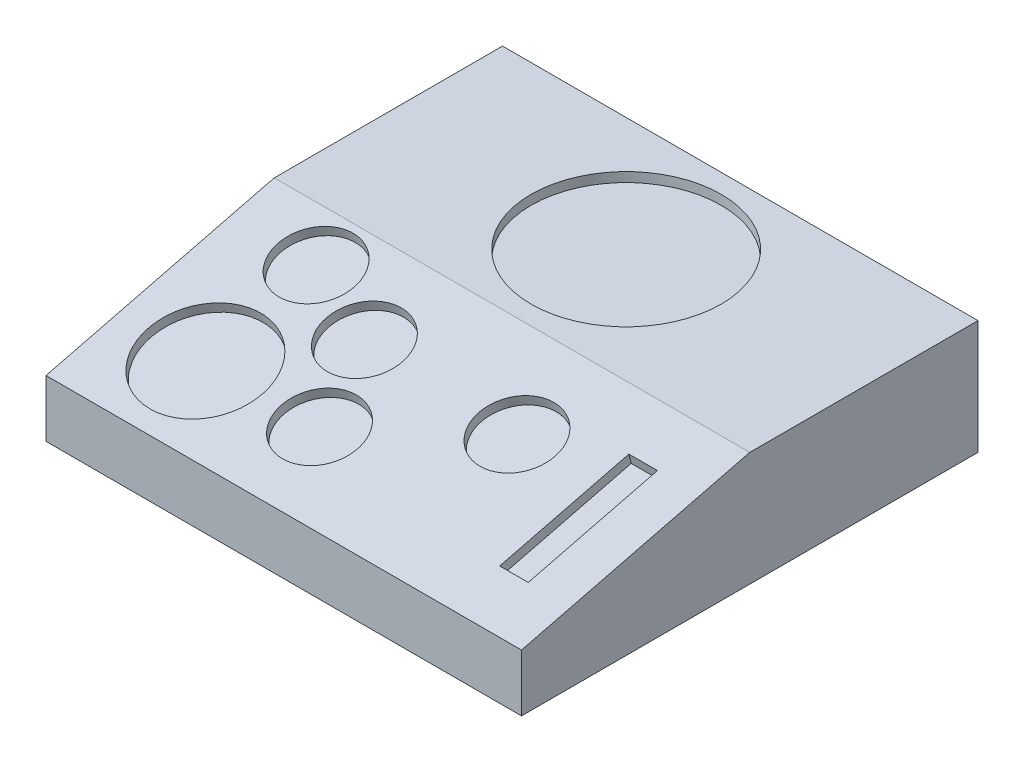
SolidWorks part; units mm, degrees
ref_plane "Alzado" through (0, 0, 0) normal (0, 0, 1) x (1, 0, 0)
ref_plane "Planta" through (0, 0, 0) normal (0, 1, 0) x (1, 0, 0)
ref_plane "Vista lateral" through (0, 0, 0) normal (1, 0, 0) x (0, 0, -1)
sketch "Croquis1" plane through (0, 0, 0) normal (0, 1, 0) x (1, 0, 0)
  line L1 (-125, -60) -> (125, -60)
  line L2 (-125, -60) -> (-125, 60)
  line L3 (-125, 60) -> (125, 60)
  line L4 (125, -60) -> (125, 60)
  line L5 (-125, -60) -> (125, 60) construction
  line L6 (-125, 60) -> (125, -60) construction
  point P0 (0, 0)
  dimension "D1" = 120
  dimension "D2" = 250
extrude "Saliente-Extruir1" add sketch "Croquis1" along normal blind 60
sketch "Croquis2" plane through (-125, 0, 0) normal (-1, 0, 0) x (0, 0, 1)
  line L0 (60, 60) -> (60, 0)
  line L1 (60, 0) -> (180, 0)
  line L2 (180, 0) -> (180, 30)
  line L3 (180, 30) -> (60, 60)
  dimension "D1" = 120
  dimension "D2" = 30
extrude "Saliente-Extruir2" add sketch "Croquis2" against normal up to surface (250 mm away) up to face at (125, 30, 0)
sketch "Croquis3" plane through (0, 60, 0) normal (0, 1, 0) x (1, 0, 0)
  circle A0 centre (0, 0) radius 50
  dimension "D1" = 100
extrude "Cortar-Extruir1" cut sketch "Croquis3" against normal blind 5
sketch "Croquis5" plane through (0, 70.5882, 17.6471) normal (0, 0.9701, 0.2425) x (-1, 0, 0)
  line L0 (37.5736, 84.9232) -> (80, 127.3496) construction
  line L1 (80, 127.3496) -> (20, 127.3496) construction
  line L2 (80, 67.3496) -> (80, 127.3496) construction
  line L3 (-125, 167.3496) -> (125, 167.3496) construction
  line L4 (125, 167.3496) -> (125, 43.6564) construction
  line L6 (-102.5, 70.503) -> (-87.5, 70.503)
  line L7 (-102.5, 70.503) -> (-102.5, 140.503)
  line L8 (-102.5, 140.503) -> (-87.5, 140.503)
  line L9 (-87.5, 70.503) -> (-87.5, 140.503)
  line L10 (-102.5, 70.503) -> (-87.5, 140.503) construction
  line L11 (-102.5, 140.503) -> (-87.5, 70.503) construction
  line L12 (-125, 43.6564) -> (-125, 167.3496) construction
  circle A0 centre (80, 127.3496) radius 30
  circle A1 centre (80, 67.3496) radius 20
  circle A2 centre (37.5736, 84.9232) radius 20
  circle A3 centre (20, 127.3496) radius 20
  circle A4 centre (-45, 87.3496) radius 20
  point P15 (-95, 105.503)
  point P22 (-125, 105.503)
  dimension "D1" = 60
  dimension "D2" = 40
  dimension "D3" = 60
  dimension "D4" = 60
  dimension "D5" = 60
  dimension "D6" = 125
  dimension "D7" = 40
  dimension "D8" = 40
  dimension "D9" = 45
  dimension "D10" = 45
  dimension "D11" = 15
  dimension "D12" = 70
  dimension "D13" = 30
extrude "Cortar-Extruir2" cut sketch "Croquis5" against normal blind 5
equation "\"D4@Croquis5\" =\"D3@Croquis5\""
equation "\"D5@Croquis5\" = \"D3@Croquis5\""
